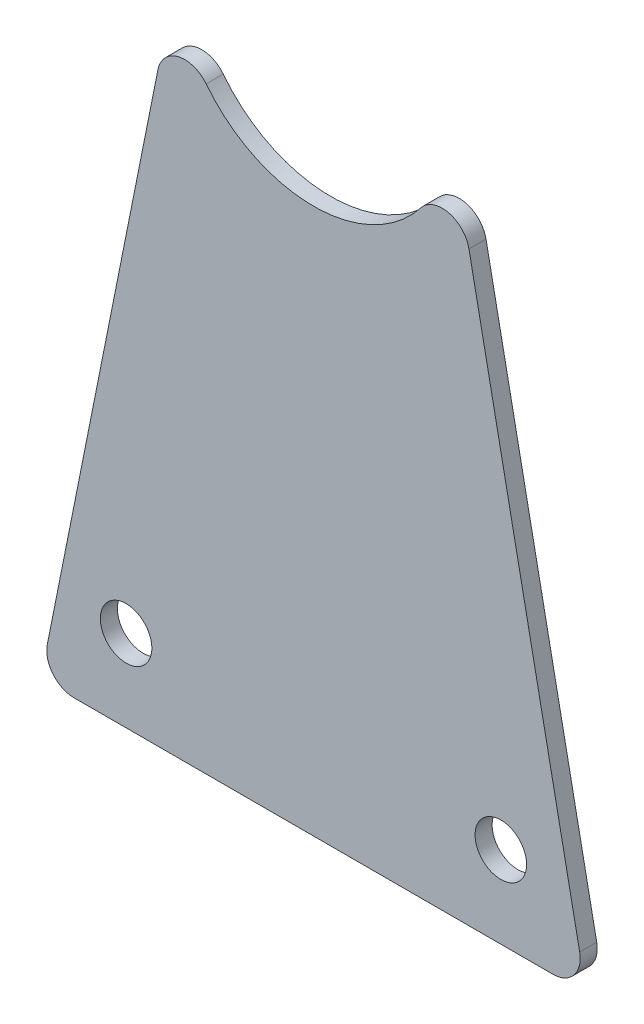
SolidWorks part; units mm, degrees
material "AISI 4130 Steel, annealed at 865C"
ref_plane "X-Y Datum" through (0, 0, 0) normal (0, 0, 1) x (1, 0, 0)
ref_plane "X-Z Datum" through (0, 0, 0) normal (0, 1, 0) x (1, 0, 0)
ref_plane "Y-Z Datum" through (0, 0, 0) normal (1, 0, 0) x (0, 0, -1)
sketch "Sketch1" plane through (0, 0, 0) normal (0, 0, 1) x (1, 0, 0)
  line L1 (0, 0) -> (0, 63.5) construction
  line L9 (-25.4, 0) -> (25.4, 0)
  line L12 (-12.7, 63.5) -> (-25.4, 0)
  line L13 (12.7, 63.5) -> (25.4, 0)
  arc A3 (-12.7, 63.5) -> (12.7, 63.5) centre (0, 63.5) ccw
  dimension "D1" = 25.4
  dimension "D2" = 50.8
  dimension "D3" = 63.5
extrude "Boss-Extrude1" add sketch "Sketch1" along normal mid plane 1.5875
hole_wizard "M4 Clearance Hole1" positions "Sketch6" profile "Sketch5" hole size "M4" standard "ANSI Metric" end condition up to next
sketch "Sketch6" plane through (0, 0, 0.7937) normal (0, 0, 1) x (1, 0, 0)
  line L0 (-23.876, 7.62) -> (23.876, 7.62) construction
  line L1 (-12.7, 63.5) -> (-25.4, 0) construction
  line L3 (25.4, 0) -> (12.7, 63.5) construction
  line L4 (-25.4, 0) -> (25.4, 0) construction
  line L6 (0, -43.0151) -> (0, 43.0151) construction
  point P12 (-17.45, 7.62)
  point P19 (17.45, 7.62)
  dimension "D1" = 7.62
  dimension "D2" = 34.9
sketch "Sketch5" plane through (17.45, 7.62, 0.7937) normal (1, 0, 0) x (0, -1, 0)
  line L0 (0, 0) -> (0, 1.5875)
  line L1 (0, 1.5875) -> (2.4, 1.5875)
  line L2 (2.4, 1.5875) -> (2.4, 0)
  line L5 (2.4, 0) -> (0, 0)
  line L11 (0, -6.35) -> (0, 107.95) construction
  dimension "Thru Hole Dia." = 4.8
  dimension "Thru Hole Depth" = 1.5875
fillet "Fillet1" radius 2.54 4 edges at (12.7, 63.5, 0) (-12.7, 63.5, 0) (25.4, 0, 0) (-25.4, 0, 0)
